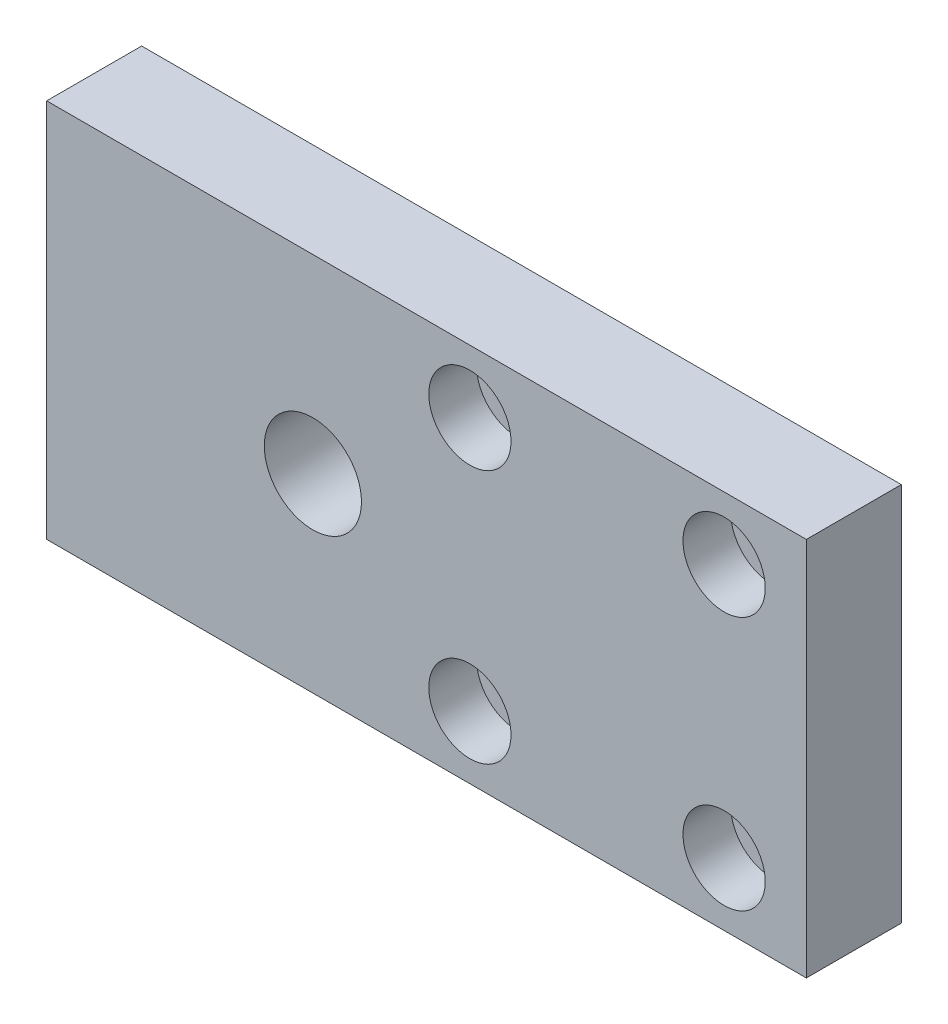
SolidWorks part; units mm, degrees
ref_plane "Alzado" through (0, 0, 0) normal (0, 0, 1) x (1, 0, 0)
ref_plane "Planta" through (0, 0, 0) normal (0, 1, 0) x (1, 0, 0)
ref_plane "Vista lateral" through (0, 0, 0) normal (1, 0, 0) x (0, 0, -1)
sketch "Croquis1" plane through (0, 0, 0) normal (0, 0, 1) x (1, 0, 0)
  line L1 (50.8, 25.4) -> (-50.8, 25.4)
  line L2 (50.8, 25.4) -> (50.8, -25.4)
  line L3 (50.8, -25.4) -> (-50.8, -25.4)
  line L4 (-50.8, 25.4) -> (-50.8, -25.4)
  line L5 (50.8, 25.4) -> (-50.8, -25.4) construction
  line L6 (50.8, -25.4) -> (-50.8, 25.4) construction
  circle A0 centre (-15.2, 0) radius 6.5
  circle A1 centre (-15.2, 0) radius 6.35 construction
  point P0 (0, 0)
  dimension "D3" = 13
  dimension "D1" = 50.8
  dimension "D2" = 101.6
extrude "Saliente-Extruir1" add sketch "Croquis1" along normal mid plane 12.7
hole_wizard "Refrentado para tornillo con cabeza hueca de M61" positions "Croquis2" profile "Croquis3" counterbore size "M6" standard "DIN" end condition through all
sketch "Croquis2" plane through (0, 0, 6.35) normal (0, 0, 1) x (1, 0, 0)
  point P2 (5.8, 17)
  point P5 (39.8, 17)
  point P8 (39.8, -17)
  point P11 (5.8, -17)
sketch "Croquis3" plane through (5.8, 17, 6.35) normal (1, 0, 0) x (0, -1, 0)
  line L0 (0, 0) -> (0, 12.7)
  line L1 (0, 12.7) -> (3.3, 12.7)
  line L3 (3.3, 12.7) -> (3.3, 6.4)
  line L4 (3.3, 6.4) -> (5.5, 6.4)
  line L5 (5.5, 6.4) -> (5.5, 0)
  line L7 (5.5, 0) -> (0, 0)
  line L11 (0, -6.35) -> (0, 107.95) construction
  dimension "Diámetro de taladro hasta el siguiente" = 6.6
  dimension "Profundidad de taladro hasta el siguiente" = 12.7
  dimension "Diámetro de refrentado" = 11
  dimension "Profundidad de refrentado" = 6.4
